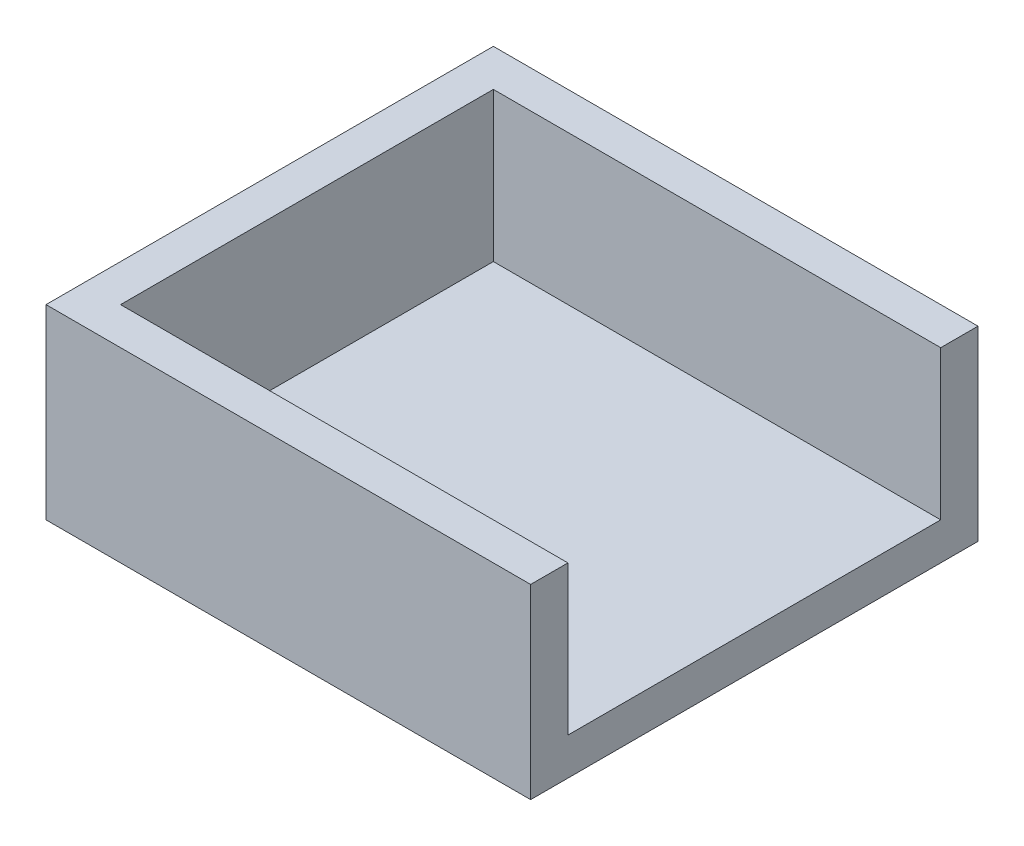
SolidWorks part; units mm, degrees
ref_plane "Front Plane" through (0, 0, 0) normal (0, 0, 1) x (1, 0, 0)
ref_plane "Top Plane" through (0, 0, 0) normal (0, 1, 0) x (1, 0, 0)
ref_plane "Right Plane" through (0, 0, 0) normal (1, 0, 0) x (0, 0, -1)
sketch "Sketch1" plane through (0, 0, 0) normal (0, 1, 0) x (1, 0, 0)
  line L1 (0, 0) -> (165.1, 0)
  line L2 (0, 0) -> (0, 152.4)
  line L3 (0, 152.4) -> (165.1, 152.4)
  line L4 (165.1, 0) -> (165.1, 152.4)
  dimension "D1" = 165.1
  dimension "D2" = 152.4
extrude "Boss-Extrude1" add sketch "Sketch1" along normal blind 63.5
sketch "Sketch2" plane through (0, 63.5, 0) normal (0, 1, 0) x (1, 0, 0)
  line L0 (165.1, 12.7) -> (12.7, 12.7)
  line L1 (165.1, 0) -> (165.1, 152.4) construction
  line L2 (0, 0) -> (165.1, 0) construction
  line L3 (12.7, 12.7) -> (12.7, 139.7)
  line L4 (12.7, 139.7) -> (165.1, 139.7)
  line L10 (0, 152.4) -> (0, 0)
  line L11 (0, 0) -> (165.1, 0)
  line L12 (165.1, 0) -> (165.1, 152.4)
  line L13 (165.1, 152.4) -> (0, 152.4)
  line L16 (165.1, 12.7) -> (165.1, 139.7)
  dimension "D1" = 12.7
  dimension "D2" = 152.4
  dimension "D3" = 127
  dimension "D4" = 0
extrude "Cut-Extrude1" cut sketch "Sketch2" against normal blind 50.8 contours L0 L3 L4 L16
